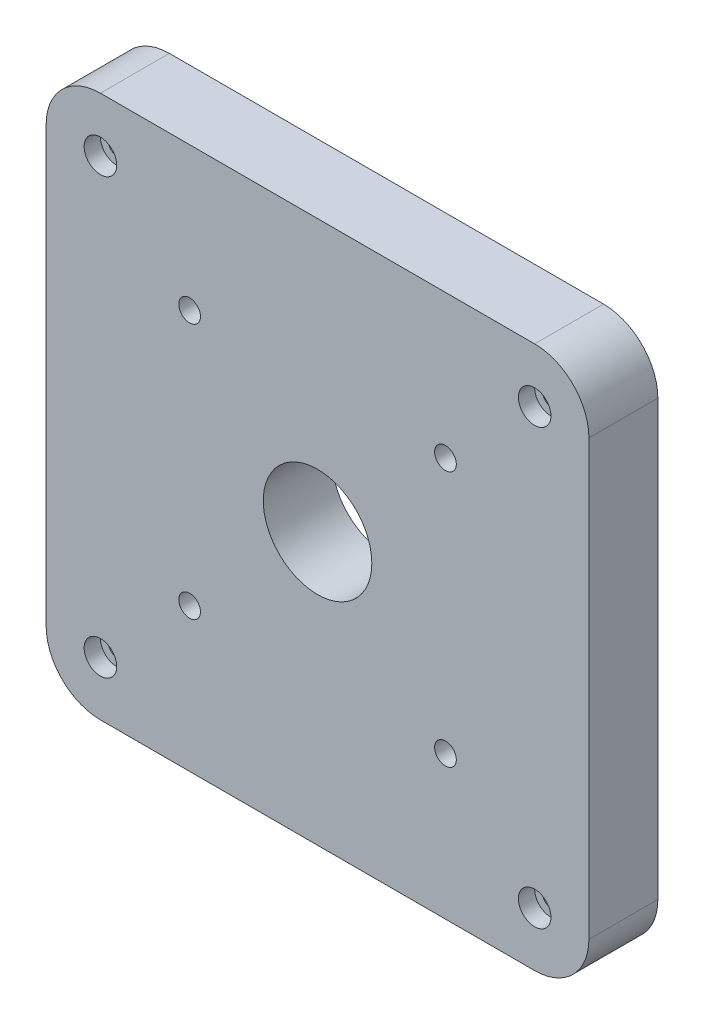
SolidWorks part; units mm, degrees
ref_plane "Front Plane" through (0, 0, 0) normal (0, 0, 1) x (1, 0, 0)
ref_plane "Top Plane" through (0, 0, 0) normal (0, 1, 0) x (1, 0, 0)
ref_plane "Right Plane" through (0, 0, 0) normal (1, 0, 0) x (0, 0, -1)
sketch "Croquis5" plane through (0, 0, 12.7) normal (0, 0, 1) x (1, 0, 0)
  line L1 (160, 0) -> (80, 0)
  line L2 (170, 10) -> (170, 90)
  line L3 (160, 100) -> (80, 100)
  line L4 (70, 10) -> (70, 90)
  arc A0 (170, 90) -> (160, 100) centre (160, 90) ccw
  arc A1 (80, 0) -> (70, 10) centre (80, 10) cw
  arc A2 (160, 0) -> (170, 10) centre (160, 10) ccw
  arc A3 (80, 100) -> (70, 90) centre (80, 90) ccw
  dimension "D1" = 10
extrude "Saliente-Extruir4" add sketch "Croquis5" along normal blind 12.7 from offset 70 separate body
sketch "Croquis8" plane through (0, 0, 95.4) normal (0, 0, 1) x (1, 0, 0)
  circle A0 centre (80, 90) radius 3
  circle A1 centre (160, 90) radius 3
  circle A2 centre (160, 10) radius 3
  circle A3 centre (80, 10) radius 3
extrude "Cortar-Extruir1" cut sketch "Croquis8" against normal blind 3
sketch "Croquis13" plane through (0, 0, 95.4) normal (0, 0, 1) x (1, 0, 0)
  circle A0 centre (80, 90) radius 1.5
  circle A1 centre (160, 90) radius 1.5
  circle A2 centre (160, 10) radius 1.5
  circle A3 centre (80, 10) radius 1.5
extrude "Cortar-Extruir4" cut sketch "Croquis13" against normal blind 30
sketch "Croquis16" plane through (0, 0, 95.4) normal (0, 0, 1) x (1, 0, 0)
  line L0 (170, 10) -> (170, 90) construction
  line L1 (80, 0) -> (160, 0) construction
  circle A5 centre (120, 50) radius 10
  circle A10 centre (96.43, 73.57) radius 2
  circle A11 centre (143.57, 73.57) radius 2
  circle A12 centre (96.43, 26.43) radius 2
  circle A13 centre (143.57, 26.43) radius 2
  dimension "D5" = 47.14
  dimension "D1" = 47.14
  dimension "D2" = 50
  dimension "D3" = 50
  dimension "D4" = 47.14
  dimension "D6" = 47.14
  dimension "D7" = 23.57
  dimension "D8" = 23.57
extrude "Cortar-Extruir6" cut sketch "Croquis16" against normal blind 31
sketch "Croquis21" plane through (0, 0, 82.7) normal (0, 0, -1) x (-1, 0, 0)
  circle A0 centre (-143.57, 73.57) radius 4
  circle A1 centre (-96.43, 73.57) radius 4
  circle A2 centre (-143.57, 26.43) radius 4
  circle A3 centre (-96.43, 26.43) radius 4
extrude "Cortar-Extruir12" cut sketch "Croquis21" against normal blind 4.5
